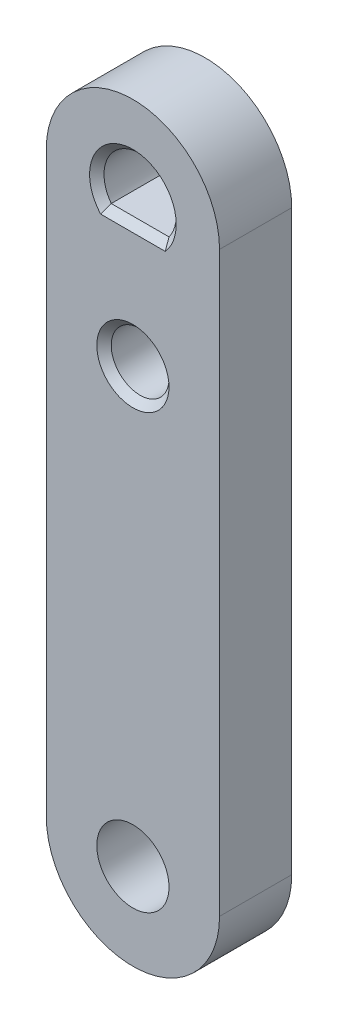
SolidWorks part; units mm, degrees
material "Stop 1060"
ref_plane "Płaszczyzna przednia" through (0, 0, 0) normal (0, 0, 1) x (1, 0, 0)
ref_plane "Płaszczyzna górna" through (0, 0, 0) normal (0, 1, 0) x (1, 0, 0)
ref_plane "Płaszczyzna prawa" through (0, 0, 0) normal (1, 0, 0) x (0, 0, -1)
sketch "Szkic1" plane through (0, 0, 0) normal (0, 0, 1) x (1, 0, 0)
  line L0 (0, 0) -> (0, -40)
  line L1 (6, -40) -> (6, 0)
  line L2 (-6, 0) -> (-6, -40)
  line L7 (-2, -1.5) -> (2, -1.5)
  arc A1 (6, 0) -> (-6, 0) centre (0, 0) ccw
  circle A2 centre (0, -40) radius 2.5
  arc A3 (-6, -40) -> (6, -40) centre (0, -40) ccw
  arc A7 (2, -1.5) -> (-2, -1.5) centre (0, 0) ccw
  circle A8 centre (0, -10) radius 2
  dimension "D1" = 5
  dimension "D2" = 12
  dimension "D4" = 5
  dimension "D5" = 12
  dimension "D6" = 1.5
  dimension "D7" = 4
  dimension "D8" = 10
  dimension "D3" = 40
extrude "Dodanie-wyciągnięcie1" add sketch "Szkic1" along normal blind 5
chamfer "Sfazowanie1" distance 0.5 angle 45 6 edges at (0, 2.5, 0) (0, 2.5, 5) (0, -1.5, 0) (0, -1.5, 5) (2, -10, 0) (2, -10, 5)
